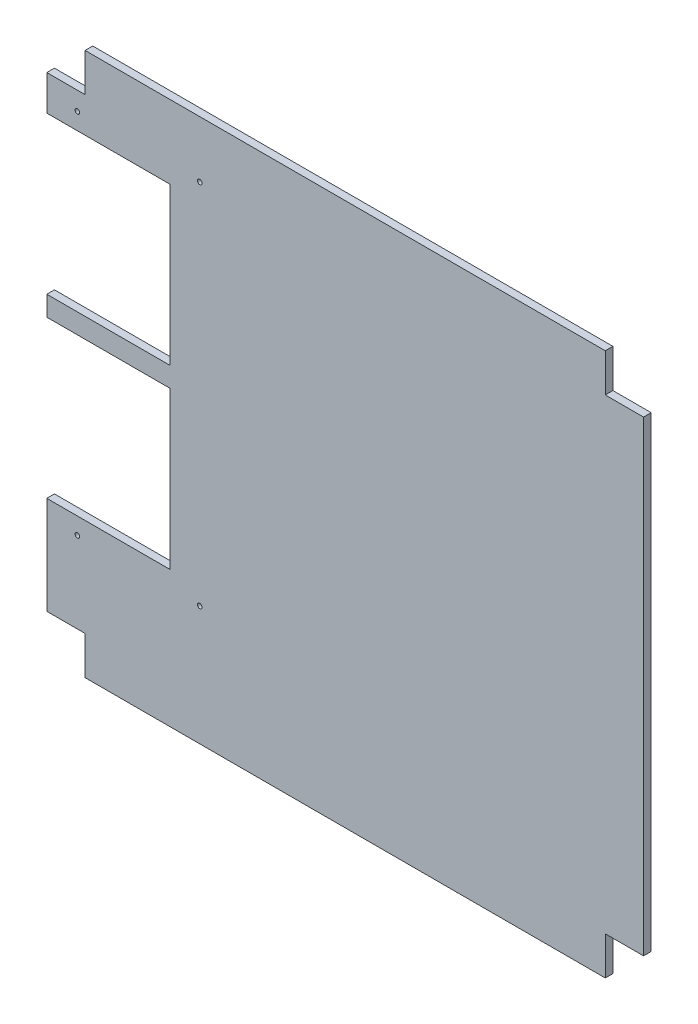
SolidWorks part; units mm, degrees
ref_plane "Plan de face" through (0, 0, 0) normal (0, 0, 1) x (1, 0, 0)
ref_plane "Plan de dessus" through (0, 0, 0) normal (0, 1, 0) x (1, 0, 0)
ref_plane "Plan de droite" through (0, 0, 0) normal (1, 0, 0) x (0, 0, -1)
sketch "Esquisse1" plane through (0, 0, 0) normal (0, 0, 1) x (1, 0, 0)
  line L1 (-195, 177.5) -> (195, 177.5)
  line L2 (-195, 177.5) -> (-195, -177.5)
  line L3 (-195, -177.5) -> (195, -177.5)
  line L4 (195, 177.5) -> (195, -177.5)
  line L5 (-195, 177.5) -> (195, -177.5) construction
  line L6 (-195, -177.5) -> (195, 177.5) construction
  point P0 (0, 0)
  dimension "D1" = 355
  dimension "D2" = 390
extrude "Boss.-Extru.1" add sketch "Esquisse1" along normal blind 5
sketch "Esquisse2" plane through (0, 0, 0) normal (0, 0, -1) x (-1, 0, 0)
  line L12 (182.5, -143.7868) -> (182.5, -126.1091) construction
  point P0 (182.5, 165)
  point P8 (182.5, -165)
  point P16 (-182.5, -165)
  point P22 (-182.5, 165)
sketch "Esquisse3" plane through (0, 0, 0) normal (0, 0, -1) x (-1, 0, 0)
  line L0 (195, 177.5) -> (195, -177.5) construction
  line L1 (114.5655, 129.5) -> (195, 129.5)
  line L2 (114.5655, 129.5) -> (114.5655, 27)
  line L3 (114.5655, 27) -> (195, 27)
  line L4 (195, 129.5) -> (195, 27)
  line L5 (95, 27) -> (195, 27) construction
  line L6 (95, -88.5) -> (195, -88.5) construction
  line L7 (114.5655, 15.3788) -> (195, 15.3788)
  line L8 (114.5655, 15.3788) -> (114.5655, -88.5)
  line L9 (114.5655, -88.5) -> (195, -88.5)
  line L10 (195, 15.3788) -> (195, -88.5)
  line L11 (-273.5117, 0) -> (306.6987, 0) construction
  line L12 (-169.97, 152.47) -> (-195, 152.47)
  line L13 (-169.97, 152.47) -> (-169.97, 177.5)
  line L14 (-169.97, 177.5) -> (-195, 177.5)
  line L15 (-195, 152.47) -> (-195, 177.5)
  line L16 (-169.97, 152.47) -> (-195, 177.5) construction
  line L17 (-169.97, 177.5) -> (-195, 152.47) construction
  line L18 (0, -232.5716) -> (0, 293.5213) construction
  line L19 (169.97, 177.5) -> (195, 177.5)
  line L20 (195, 152.47) -> (195, 177.5)
  line L21 (169.97, 152.47) -> (195, 152.47)
  line L22 (169.97, 152.47) -> (169.97, 177.5)
  line L23 (169.97, -152.47) -> (169.97, -177.5)
  line L24 (169.97, -152.47) -> (195, -152.47)
  line L25 (195, -152.47) -> (195, -177.5)
  line L26 (169.97, -177.5) -> (195, -177.5)
  line L27 (-169.97, -177.5) -> (-195, -177.5)
  line L28 (-195, -152.47) -> (-195, -177.5)
  line L29 (-169.97, -152.47) -> (-195, -152.47)
  line L30 (-169.97, -152.47) -> (-169.97, -177.5)
  point P4 (-182.485, 164.985)
  dimension "D1" = 25.03
  dimension "D2" = 25.03
extrude "Enlèv. mat.-Extru.1" cut sketch "Esquisse3" against normal blind 10
sketch "Esquisse4" plane through (0, 15.3788, 0) normal (0, -1, 0) x (1, 0, 0)
  line L4 (-114.5655, 5) -> (-195, 5)
  line L5 (-195, 5) -> (-195, 0)
  line L6 (-195, 0) -> (-114.5655, 0)
  line L7 (-114.5655, 0) -> (-114.5655, 5)
  line L8 (-114.5655, 5) -> (-195, 5)
  line L9 (-195, 5) -> (-195, 0)
  line L10 (-195, 0) -> (-114.5655, 0)
  line L11 (-114.5655, 0) -> (-114.5655, 5)
  dimension "D1" = 0
extrude "Boss.-Extru.2" add sketch "Esquisse4" along normal blind 1.38
sketch "Esquisse9" plane through (0, 0, 0) normal (0, 0, -1) x (-1, 0, 0)
  line L0 (195, -88.5) -> (195, -152.47) construction
  line L1 (195, -152.47) -> (169.97, -152.47) construction
  line L2 (135, 8.0035) -> (135, -133.665) construction
  line L3 (50.9056, 20.5) -> (405.098, 20.5) construction
  circle A0 centre (175, -99.5) radius 1.5
  circle A1 centre (95, -99.5) radius 1.5
  circle A2 centre (95, 140.5) radius 1.5
  circle A3 centre (175, 140.5) radius 1.5
  dimension "D3" = 3
  dimension "D1" = 20
  dimension "D2" = 52.97
  dimension "D4" = 40
  dimension "D5" = 120
extrude "Enlèv. mat.-Extru.2" cut sketch "Esquisse9" against normal through all
